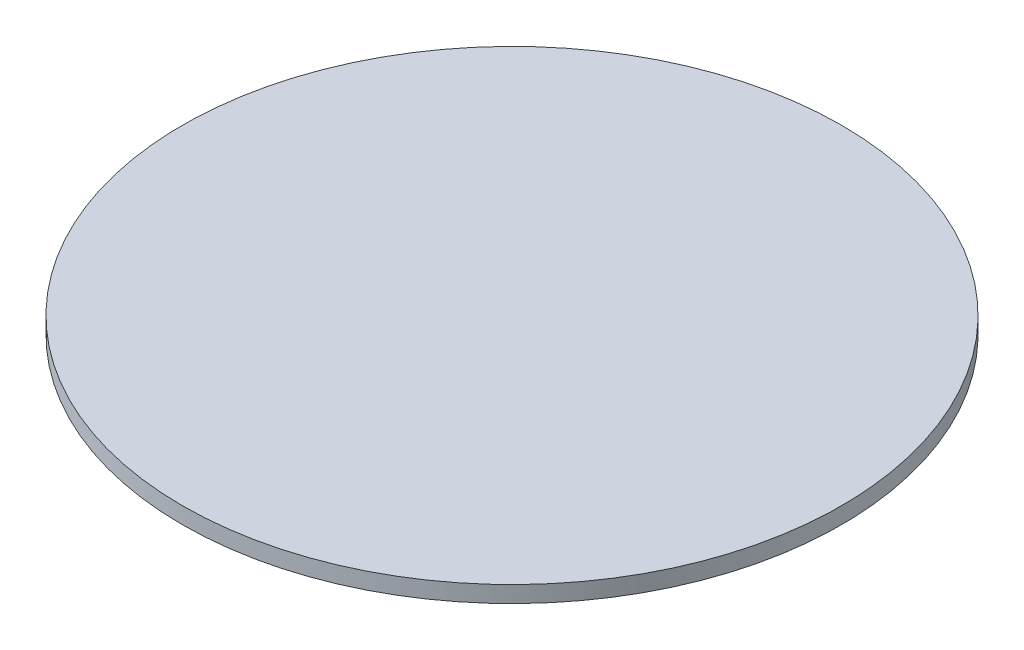
SolidWorks part; units mm, degrees
ref_plane "前视基准面" through (0, 0, 0) normal (0, 0, 1) x (1, 0, 0)
ref_plane "上视基准面" through (0, 0, 0) normal (0, 1, 0) x (1, 0, 0)
ref_plane "右视基准面" through (0, 0, 0) normal (1, 0, 0) x (0, 0, -1)
sketch "草图1" plane through (0, 0, 0) normal (0, 1, 0) x (1, 0, 0)
  circle A0 centre (0, 0) radius 20
  dimension "D1" = 40
extrude "凸台-拉伸1" add sketch "草图1" along normal blind 1
